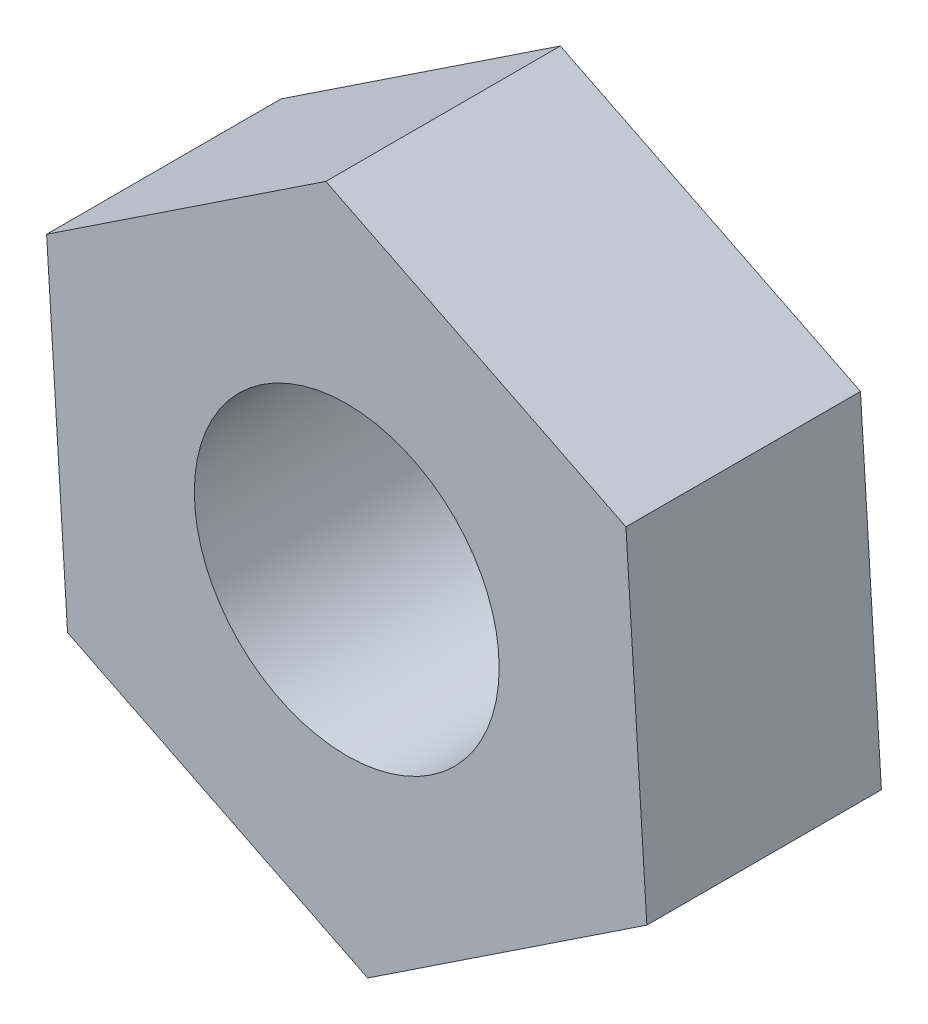
SolidWorks part; units mm, degrees
ref_plane "Front Plane" through (0, 0, 0) normal (0, 0, 1) x (1, 0, 0)
ref_plane "Top Plane" through (0, 0, 0) normal (0, 1, 0) x (1, 0, 0)
ref_plane "Right Plane" through (0, 0, 0) normal (1, 0, 0) x (0, 0, -1)
sketch "Sketch1" plane through (0, 0, 0) normal (0, 0, 1) x (1, 0, 0)
  line L1 (-2.3809, -1.5808) -> (0.1785, -2.8523)
  line L2 (0.1785, -2.8523) -> (2.5594, -1.2715)
  line L3 (2.5594, -1.2715) -> (2.3809, 1.5808)
  line L4 (2.3809, 1.5808) -> (-0.1785, 2.8523)
  line L5 (-0.1785, 2.8523) -> (-2.5594, 1.2715)
  line L6 (-2.5594, 1.2715) -> (-2.3809, -1.5808)
  circle A0 centre (0, 0) radius 2.475 construction
  dimension "D1" = 4.95
extrude "Boss-Extrude1" add sketch "Sketch1" along normal blind 2
sketch "Sketch2" plane through (0, 0, 2) normal (0, 0, 1) x (1, 0, 0)
  circle A0 centre (0, 0) radius 1.3
  dimension "D1" = 2.6
extrude "Cut-Extrude1" cut sketch "Sketch2" against normal through all
